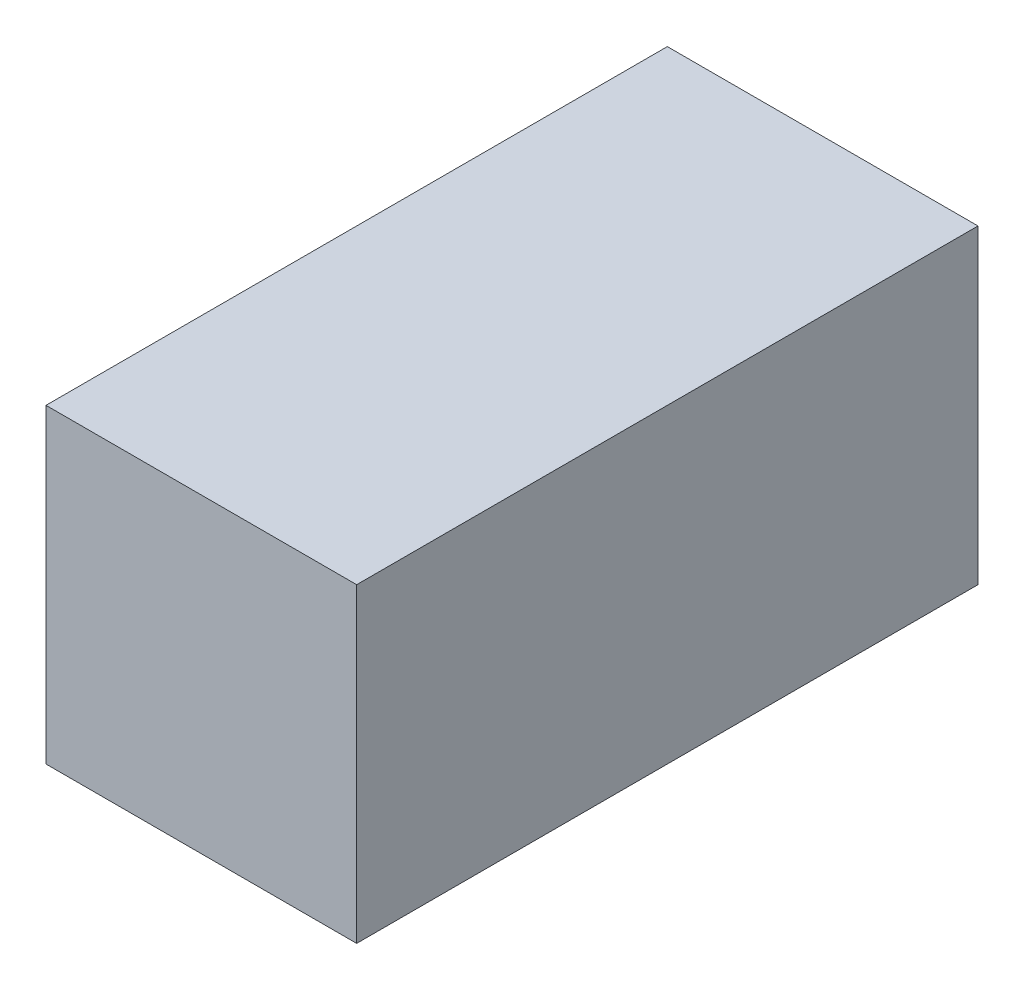
SolidWorks part; units mm, degrees
ref_plane "Alzado" through (0, 0, 0) normal (0, 0, 1) x (1, 0, 0)
ref_plane "Planta" through (0, 0, 0) normal (0, 1, 0) x (1, 0, 0)
ref_plane "Vista lateral" through (0, 0, 0) normal (1, 0, 0) x (0, 0, -1)
sketch "Croquis1" plane through (0, 0, 0) normal (0, 0, 1) x (1, 0, 0)
  line L1 (-37.5, -37.5) -> (37.5, -37.5)
  line L2 (-37.5, -37.5) -> (-37.5, 37.5)
  line L3 (-37.5, 37.5) -> (37.5, 37.5)
  line L4 (37.5, -37.5) -> (37.5, 37.5)
  line L5 (-37.5, -37.5) -> (37.5, 37.5) construction
  line L6 (-37.5, 37.5) -> (37.5, -37.5) construction
  point P0 (0, 0)
  dimension "D1" = 75
  dimension "D2" = 75
extrude "Saliente-Extruir1" add sketch "Croquis1" along normal blind 150
